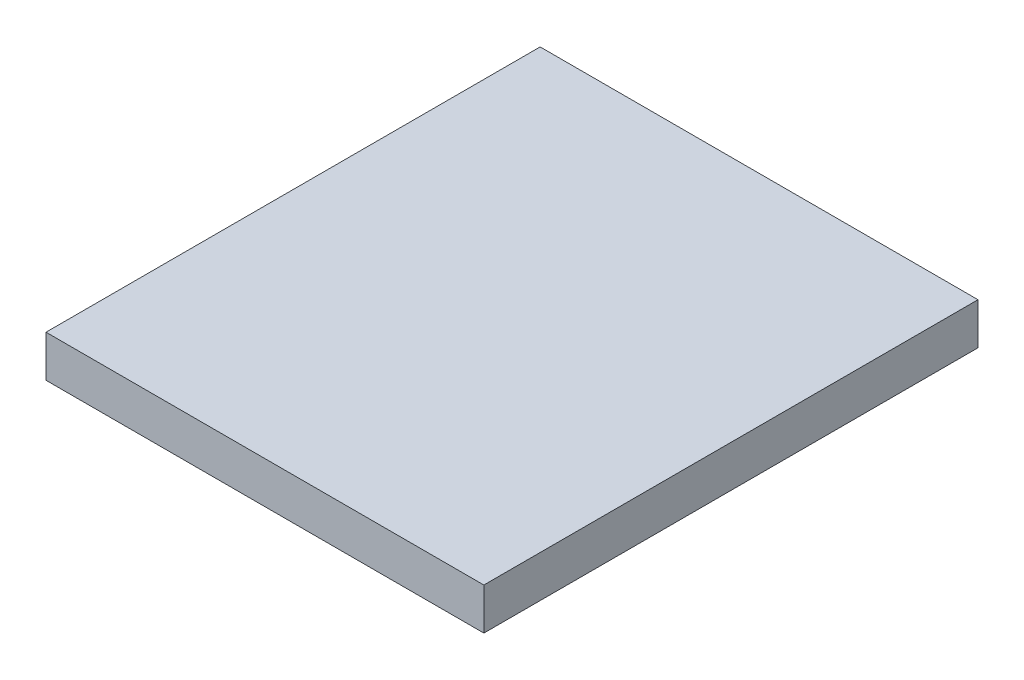
SolidWorks part; units mm, degrees
ref_plane "Front Plane" through (0, 0, 0) normal (0, 0, 1) x (1, 0, 0)
ref_plane "Top Plane" through (0, 0, 0) normal (0, 1, 0) x (1, 0, 0)
ref_plane "Right Plane" through (0, 0, 0) normal (1, 0, 0) x (0, 0, -1)
sketch "Sketch1" plane through (0, 0, 0) normal (0, 0, 1) x (1, 0, 0)
  line L0 (-100.1317, 5) -> (100.1317, 5) construction
  line L1 (-100.1317, 5) -> (100.1317, 5)
  line L2 (100.1317, 5) -> (100.1317, -14.05)
  line L3 (100.1317, -14.05) -> (-100.1317, -14.05)
  line L4 (-100.1317, -14.05) -> (-100.1317, 5)
extrude "Boss-Extrude1" add sketch "Sketch1" along normal up to surface (226 mm away)
